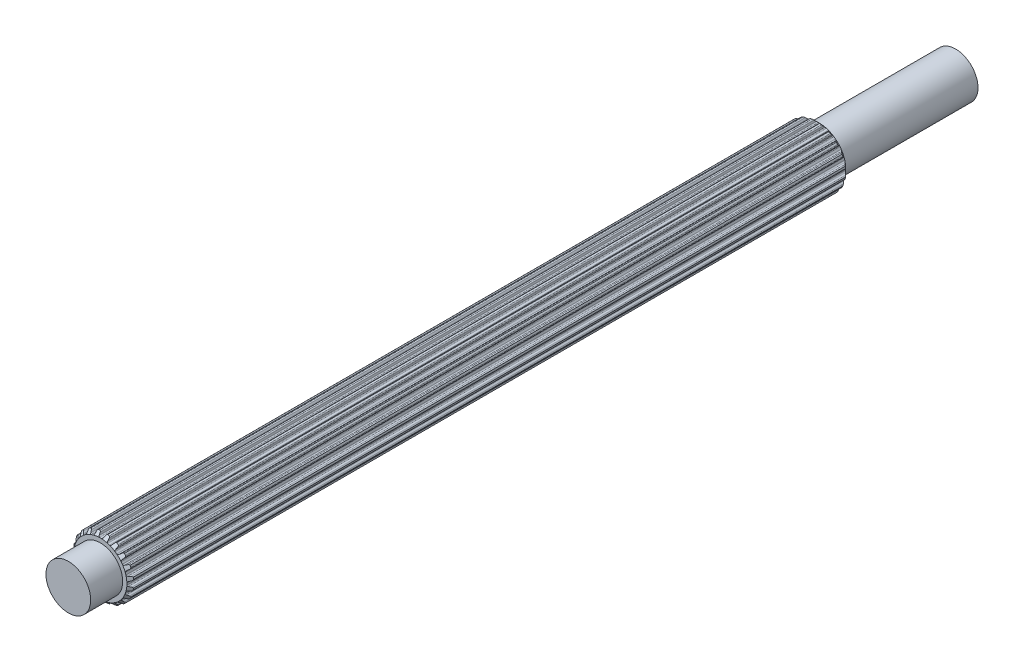
SolidWorks part; units mm, degrees
ref_plane "Front Plane" through (0, 0, 0) normal (0, 0, 1) x (1, 0, 0)
ref_plane "Top Plane" through (0, 0, 0) normal (0, 1, 0) x (1, 0, 0)
ref_plane "Right Plane" through (0, 0, 0) normal (1, 0, 0) x (0, 0, -1)
sketch "Sketch1" plane through (0, 0, 0) normal (0, 0, 1) x (1, 0, 0)
  line L0 (-0.1069, 2.9699) -> (0.1069, 2.9699)
  line L1 (0.3159, 3.2375) -> (0.2537, 3.0575)
  line L2 (-0.2964, 3.2367) -> (-0.2318, 3.0575)
  line L3 (-0.2964, 3.2367) -> (0.3159, 3.2375) construction
  line L4 (0, 3.3252) -> (0, 0) construction
  line L5 (-0.2318, 3.0575) -> (0.2537, 3.0575) construction
  line L6 (-0.4281, 3.3241) -> (0.4281, 3.3263) construction
  line L7 (0.7183, 3.1698) -> (0.7244, 2.9795)
  line L8 (0.816, 2.8576) -> (1.0195, 2.7915)
  line L9 (1.3009, 2.9815) -> (1.1862, 2.8295)
  line L10 (1.6627, 2.7927) -> (1.6097, 2.6099)
  line L11 (1.6591, 2.4655) -> (1.8322, 2.3398)
  line L12 (2.1585, 2.4335) -> (2.0025, 2.3245)
  line L13 (2.4443, 2.1423) -> (2.3374, 1.9847)
  line L14 (2.3398, 1.8322) -> (2.4655, 1.6591)
  line L15 (2.8049, 1.6474) -> (2.6228, 1.5919)
  line L16 (2.9866, 1.2821) -> (2.8363, 1.1653)
  line L17 (2.7915, 1.0195) -> (2.8576, 0.816)
  line L18 (3.1767, 0.7) -> (2.9863, 0.7035)
  line L19 (3.2367, 0.2964) -> (3.0575, 0.2318)
  line L20 (2.9699, 0.1069) -> (2.9699, -0.1069)
  line L21 (3.2375, -0.3159) -> (3.0575, -0.2537)
  line L22 (3.1698, -0.7183) -> (2.9795, -0.7244)
  line L23 (2.8576, -0.816) -> (2.7915, -1.0195)
  line L24 (2.9815, -1.3009) -> (2.8295, -1.1862)
  line L25 (2.7927, -1.6627) -> (2.6099, -1.6097)
  line L26 (2.4655, -1.6591) -> (2.3398, -1.8322)
  line L27 (2.4335, -2.1585) -> (2.3245, -2.0025)
  line L28 (2.1423, -2.4443) -> (1.9847, -2.3374)
  line L29 (1.8322, -2.3398) -> (1.6591, -2.4655)
  line L30 (1.6474, -2.8049) -> (1.5919, -2.6228)
  line L31 (1.2821, -2.9866) -> (1.1653, -2.8363)
  line L32 (1.0195, -2.7915) -> (0.816, -2.8576)
  line L33 (0.7, -3.1767) -> (0.7035, -2.9863)
  line L34 (0.2964, -3.2367) -> (0.2318, -3.0575)
  line L35 (0.1069, -2.9699) -> (-0.1069, -2.9699)
  line L36 (-0.3159, -3.2375) -> (-0.2537, -3.0575)
  line L37 (-0.7183, -3.1698) -> (-0.7244, -2.9795)
  line L38 (-0.816, -2.8576) -> (-1.0195, -2.7915)
  line L39 (-1.3009, -2.9815) -> (-1.1862, -2.8295)
  line L40 (-1.6627, -2.7927) -> (-1.6097, -2.6099)
  line L41 (-1.6591, -2.4655) -> (-1.8322, -2.3398)
  line L42 (-2.1585, -2.4335) -> (-2.0025, -2.3245)
  line L43 (-2.4443, -2.1423) -> (-2.3374, -1.9847)
  line L44 (-2.3398, -1.8322) -> (-2.4655, -1.6591)
  line L45 (-2.8049, -1.6474) -> (-2.6228, -1.5919)
  line L46 (-2.9866, -1.2821) -> (-2.8363, -1.1653)
  line L47 (-2.7915, -1.0195) -> (-2.8576, -0.816)
  line L48 (-3.1767, -0.7) -> (-2.9863, -0.7035)
  line L49 (-3.2367, -0.2964) -> (-3.0575, -0.2318)
  line L50 (-2.9699, -0.1069) -> (-2.9699, 0.1069)
  line L51 (-3.2375, 0.3159) -> (-3.0575, 0.2537)
  line L52 (-3.1698, 0.7183) -> (-2.9795, 0.7244)
  line L53 (-2.8576, 0.816) -> (-2.7915, 1.0195)
  line L54 (-2.9815, 1.3009) -> (-2.8295, 1.1862)
  line L55 (-2.7927, 1.6627) -> (-2.6099, 1.6097)
  line L56 (-2.4655, 1.6591) -> (-2.3398, 1.8322)
  line L57 (-2.4335, 2.1585) -> (-2.3245, 2.0025)
  line L58 (-2.1423, 2.4443) -> (-1.9847, 2.3374)
  line L59 (-1.8322, 2.3398) -> (-1.6591, 2.4655)
  line L60 (-1.6474, 2.8049) -> (-1.5919, 2.6228)
  line L61 (-1.2821, 2.9866) -> (-1.1653, 2.8363)
  line L62 (-1.0195, 2.7915) -> (-0.816, 2.8576)
  line L63 (-0.7, 3.1767) -> (-0.7035, 2.9863)
  line L64 (0.4281, 3.3263) -> (0.62, 3.2938)
  line L65 (1.4351, 3.0312) -> (1.6075, 2.9409)
  line L66 (2.3015, 2.4394) -> (2.4376, 2.3003)
  line L67 (2.9427, 1.6088) -> (3.0291, 1.4344)
  line L68 (3.2958, 0.6207) -> (3.3241, 0.4281)
  line L69 (3.3263, -0.4281) -> (3.2938, -0.62)
  line L70 (3.0312, -1.4351) -> (2.9409, -1.6075)
  line L71 (2.4394, -2.3015) -> (2.3003, -2.4376)
  line L72 (1.6088, -2.9427) -> (1.4344, -3.0291)
  line L73 (0.6207, -3.2958) -> (0.4281, -3.3241)
  line L74 (-0.4281, -3.3263) -> (-0.62, -3.2938)
  line L75 (-1.4351, -3.0312) -> (-1.6075, -2.9409)
  line L76 (-2.3015, -2.4394) -> (-2.4376, -2.3003)
  line L77 (-2.9427, -1.6088) -> (-3.0291, -1.4344)
  line L78 (-3.2958, -0.6207) -> (-3.3241, -0.4281)
  line L79 (-3.3263, 0.4281) -> (-3.2938, 0.62)
  line L80 (-3.0312, 1.4351) -> (-2.9409, 1.6075)
  line L81 (-2.4394, 2.3015) -> (-2.3003, 2.4376)
  line L82 (-1.6088, 2.9427) -> (-1.4344, 3.0291)
  line L83 (-0.6207, 3.2958) -> (-0.4281, 3.3241)
  arc A0 (0.2537, 3.0575) -> (0.1069, 2.9699) centre (0.1283, 3.1009) cw
  arc A1 (-0.2318, 3.0575) -> (-0.1069, 2.9699) centre (-0.1069, 3.1026) ccw
  arc A2 (0.62, 3.2938) -> (0.7183, 3.1698) centre (0.5856, 3.1656) cw
  arc A3 (0.7244, 2.9795) -> (0.816, 2.8576) centre (0.857, 2.9838) ccw
  arc A4 (-0.4281, 3.3241) -> (-0.2964, 3.2367) centre (-0.4213, 3.1916) cw
  arc A5 (0.4281, 3.3263) -> (0.3159, 3.2375) centre (0.4413, 3.1942) ccw
  arc A6 (1.1862, 2.8295) -> (1.0195, 2.7915) centre (1.0802, 2.9095) cw
  arc A7 (1.4351, 3.0312) -> (1.3009, 2.9815) centre (1.4068, 2.9015) ccw
  arc A8 (1.6075, 2.9409) -> (1.6627, 2.7927) centre (1.5352, 2.8297) cw
  arc A9 (1.6097, 2.6099) -> (1.6591, 2.4655) centre (1.7371, 2.5729) ccw
  arc A10 (2.0025, 2.3245) -> (1.8322, 2.3398) centre (1.9264, 2.4332) cw
  arc A11 (2.3015, 2.4394) -> (2.1585, 2.4335) centre (2.2346, 2.3248) ccw
  arc A12 (2.4376, 2.3003) -> (2.4443, 2.1423) centre (2.3345, 2.2168) cw
  arc A13 (2.3374, 1.9847) -> (2.3398, 1.8322) centre (2.4472, 1.9102) ccw
  arc A14 (2.6228, 1.5919) -> (2.4655, 1.6591) centre (2.5841, 1.7189) cw
  arc A15 (2.9427, 1.6088) -> (2.8049, 1.6474) centre (2.8436, 1.5205) ccw
  arc A16 (3.0291, 1.4344) -> (2.9866, 1.2821) centre (2.9052, 1.3869) cw
  arc A17 (2.8363, 1.1653) -> (2.7915, 1.0195) centre (2.9177, 1.0605) ccw
  arc A18 (2.9863, 0.7035) -> (2.8576, 0.816) centre (2.9887, 0.8362) cw
  arc A19 (3.2958, 0.6207) -> (3.1767, 0.7) centre (3.1743, 0.5673) ccw
  arc A20 (3.3241, 0.4281) -> (3.2367, 0.2964) centre (3.1916, 0.4213) cw
  arc A21 (3.0575, 0.2318) -> (2.9699, 0.1069) centre (3.1026, 0.1069) ccw
  arc A22 (3.0575, -0.2537) -> (2.9699, -0.1069) centre (3.1009, -0.1283) cw
  arc A23 (3.3263, -0.4281) -> (3.2375, -0.3159) centre (3.1942, -0.4413) ccw
  arc A24 (3.2938, -0.62) -> (3.1698, -0.7183) centre (3.1656, -0.5856) cw
  arc A25 (2.9795, -0.7244) -> (2.8576, -0.816) centre (2.9838, -0.857) ccw
  arc A26 (2.8295, -1.1862) -> (2.7915, -1.0195) centre (2.9095, -1.0802) cw
  arc A27 (3.0312, -1.4351) -> (2.9815, -1.3009) centre (2.9015, -1.4068) ccw
  arc A28 (2.9409, -1.6075) -> (2.7927, -1.6627) centre (2.8297, -1.5352) cw
  arc A29 (2.6099, -1.6097) -> (2.4655, -1.6591) centre (2.5729, -1.7371) ccw
  arc A30 (2.3245, -2.0025) -> (2.3398, -1.8322) centre (2.4332, -1.9264) cw
  arc A31 (2.4394, -2.3015) -> (2.4335, -2.1585) centre (2.3248, -2.2346) ccw
  arc A32 (2.3003, -2.4376) -> (2.1423, -2.4443) centre (2.2168, -2.3345) cw
  arc A33 (1.9847, -2.3374) -> (1.8322, -2.3398) centre (1.9102, -2.4472) ccw
  arc A34 (1.5919, -2.6228) -> (1.6591, -2.4655) centre (1.7189, -2.5841) cw
  arc A35 (1.6088, -2.9427) -> (1.6474, -2.8049) centre (1.5205, -2.8436) ccw
  arc A36 (1.4344, -3.0291) -> (1.2821, -2.9866) centre (1.3869, -2.9052) cw
  arc A37 (1.1653, -2.8363) -> (1.0195, -2.7915) centre (1.0605, -2.9177) ccw
  arc A38 (0.7035, -2.9863) -> (0.816, -2.8576) centre (0.8362, -2.9887) cw
  arc A39 (0.6207, -3.2958) -> (0.7, -3.1767) centre (0.5673, -3.1743) ccw
  arc A40 (0.4281, -3.3241) -> (0.2964, -3.2367) centre (0.4213, -3.1916) cw
  arc A41 (0.2318, -3.0575) -> (0.1069, -2.9699) centre (0.1069, -3.1026) ccw
  arc A42 (-0.2537, -3.0575) -> (-0.1069, -2.9699) centre (-0.1283, -3.1009) cw
  arc A43 (-0.4281, -3.3263) -> (-0.3159, -3.2375) centre (-0.4413, -3.1942) ccw
  arc A44 (-0.62, -3.2938) -> (-0.7183, -3.1698) centre (-0.5856, -3.1656) cw
  arc A45 (-0.7244, -2.9795) -> (-0.816, -2.8576) centre (-0.857, -2.9838) ccw
  arc A46 (-1.1862, -2.8295) -> (-1.0195, -2.7915) centre (-1.0802, -2.9095) cw
  arc A47 (-1.4351, -3.0312) -> (-1.3009, -2.9815) centre (-1.4068, -2.9015) ccw
  arc A48 (-1.6075, -2.9409) -> (-1.6627, -2.7927) centre (-1.5352, -2.8297) cw
  arc A49 (-1.6097, -2.6099) -> (-1.6591, -2.4655) centre (-1.7371, -2.5729) ccw
  arc A50 (-2.0025, -2.3245) -> (-1.8322, -2.3398) centre (-1.9264, -2.4332) cw
  arc A51 (-2.3015, -2.4394) -> (-2.1585, -2.4335) centre (-2.2346, -2.3248) ccw
  arc A52 (-2.4376, -2.3003) -> (-2.4443, -2.1423) centre (-2.3345, -2.2168) cw
  arc A53 (-2.3374, -1.9847) -> (-2.3398, -1.8322) centre (-2.4472, -1.9102) ccw
  arc A54 (-2.6228, -1.5919) -> (-2.4655, -1.6591) centre (-2.5841, -1.7189) cw
  arc A55 (-2.9427, -1.6088) -> (-2.8049, -1.6474) centre (-2.8436, -1.5205) ccw
  arc A56 (-3.0291, -1.4344) -> (-2.9866, -1.2821) centre (-2.9052, -1.3869) cw
  arc A57 (-2.8363, -1.1653) -> (-2.7915, -1.0195) centre (-2.9177, -1.0605) ccw
  arc A58 (-2.9863, -0.7035) -> (-2.8576, -0.816) centre (-2.9887, -0.8362) cw
  arc A59 (-3.2958, -0.6207) -> (-3.1767, -0.7) centre (-3.1743, -0.5673) ccw
  arc A60 (-3.3241, -0.4281) -> (-3.2367, -0.2964) centre (-3.1916, -0.4213) cw
  arc A61 (-3.0575, -0.2318) -> (-2.9699, -0.1069) centre (-3.1026, -0.1069) ccw
  arc A62 (-3.0575, 0.2537) -> (-2.9699, 0.1069) centre (-3.1009, 0.1283) cw
  arc A63 (-3.3263, 0.4281) -> (-3.2375, 0.3159) centre (-3.1942, 0.4413) ccw
  arc A64 (-3.2938, 0.62) -> (-3.1698, 0.7183) centre (-3.1656, 0.5856) cw
  arc A65 (-2.9795, 0.7244) -> (-2.8576, 0.816) centre (-2.9838, 0.857) ccw
  arc A66 (-2.8295, 1.1862) -> (-2.7915, 1.0195) centre (-2.9095, 1.0802) cw
  arc A67 (-3.0312, 1.4351) -> (-2.9815, 1.3009) centre (-2.9015, 1.4068) ccw
  arc A68 (-2.9409, 1.6075) -> (-2.7927, 1.6627) centre (-2.8297, 1.5352) cw
  arc A69 (-2.6099, 1.6097) -> (-2.4655, 1.6591) centre (-2.5729, 1.7371) ccw
  arc A70 (-2.3245, 2.0025) -> (-2.3398, 1.8322) centre (-2.4332, 1.9264) cw
  arc A71 (-2.4394, 2.3015) -> (-2.4335, 2.1585) centre (-2.3248, 2.2346) ccw
  arc A72 (-2.3003, 2.4376) -> (-2.1423, 2.4443) centre (-2.2168, 2.3345) cw
  arc A73 (-1.9847, 2.3374) -> (-1.8322, 2.3398) centre (-1.9102, 2.4472) ccw
  arc A74 (-1.5919, 2.6228) -> (-1.6591, 2.4655) centre (-1.7189, 2.5841) cw
  arc A75 (-1.6088, 2.9427) -> (-1.6474, 2.8049) centre (-1.5205, 2.8436) ccw
  arc A76 (-1.4344, 3.0291) -> (-1.2821, 2.9866) centre (-1.3869, 2.9052) cw
  arc A77 (-1.1653, 2.8363) -> (-1.0195, 2.7915) centre (-1.0605, 2.9177) ccw
  arc A78 (-0.7035, 2.9863) -> (-0.816, 2.8576) centre (-0.8362, 2.9887) cw
  arc A79 (-0.6207, 3.2958) -> (-0.7, 3.1767) centre (-0.5673, 3.1743) ccw
  point P14 (0, 2.9699)
  point P247 (0, 0)
  dimension "D4" = 0.1327
  dimension "D8" = 20
  dimension "D1" = 2.9699
  dimension "D2" = 0.2139
  dimension "D3" = 0.1904
  dimension "D5" = 0.0877
  dimension "D6" = 0.4855
  dimension "D7" = 0.8563
extrude "Boss-Extrude1" add sketch "Sketch1" along normal blind 46.0477 and the other way blind 34.3637
sketch "Sketch2" plane through (0, 0, 0) normal (0, 0, 1) x (1, 0, 0)
  circle A0 centre (0, 0) radius 2.5019
  dimension "D1" = 5.0038
extrude "Boss-Extrude2" add sketch "Sketch2" along normal mid plane 99.2581
sketch "Sketch4" plane through (0, 0, 49.6291) normal (0, 0, 1) x (1, 0, 0)
  circle A0 centre (0, 0) radius 2.5019 construction
  point P0 (0, 0)
sketch "Sketch5" plane through (0, 0, -49.6291) normal (0, 0, -1) x (-1, 0, 0)
  circle A0 centre (0, 0) radius 2.5019 construction
  point P0 (0, 0)
sketch "Sketch3" plane through (0, 0, 0) normal (1, 0, 0) x (0, 0, -1)
  line L0 (-44.9164, 4.1011) -> (-46.0477, 2.9699)
  line L1 (-46.0477, 2.9699) -> (-46.0477, 4.1011)
  line L2 (-46.0477, 4.1011) -> (-44.9164, 4.1011)
  line L3 (-46.0477, 2.5019) -> (-46.0477, -2.5019) construction
  line L5 (-14.3608, 0) -> (13.2171, 0) construction
  line L7 (34.3637, 31.0775) -> (34.3637, 2.9699)
  line L8 (34.3637, 2.9699) -> (20.3098, 17.0237)
  line L9 (20.3098, 17.0237) -> (34.3637, 31.0775)
  line L10 (34.3637, -2.5019) -> (34.3637, 2.5019) construction
  point P6 (-4.866, 6.1438)
  dimension "D1" = 45
  dimension "D2" = 45
revolve "Cut-Revolve1" cut sketch "Sketch3" angle 360 about L5
sketch "Sketch6" plane through (0, 0, 0) normal (0, 1, 0) x (1, 0, 0)
  line L0 (-15.5223, 0) -> (15.5223, 0) construction
